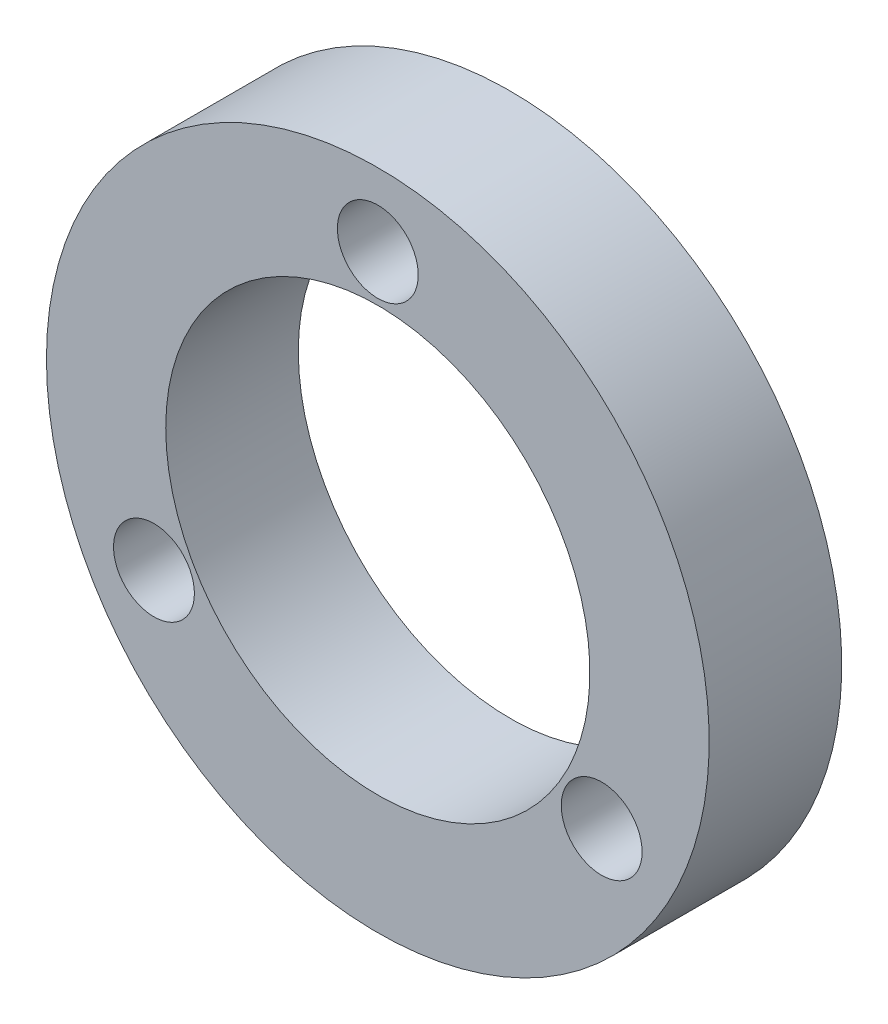
SolidWorks part; units mm, degrees
ref_plane "Front Plane" through (0, 0, 0) normal (0, 0, 1) x (1, 0, 0)
ref_plane "Top Plane" through (0, 0, 0) normal (0, 1, 0) x (1, 0, 0)
ref_plane "Right Plane" through (0, 0, 0) normal (1, 0, 0) x (0, 0, -1)
sketch "Sketch1" plane through (0, 0, 0) normal (0, 0, 1) x (1, 0, 0)
  circle A0 centre (0, 0) radius 8
  circle A1 centre (0, 0) radius 12.5
  dimension "D1" = 16
  dimension "D2" = 25
extrude "Boss-Extrude1" add sketch "Sketch1" along normal blind 5
sketch "Sketch2" plane through (0, 0, 5) normal (0, 0, 1) x (1, 0, 0)
  circle A1 centre (0, 9.75) radius 1.525
  circle A2 centre (8.4437, -4.875) radius 1.525
  circle A3 centre (-8.4437, -4.875) radius 1.525
  point P11 (0, 0)
  dimension "D2" = 3.05
  dimension "D3" = 3
extrude "Cut-Extrude1" cut sketch "Sketch2" against normal up to next
